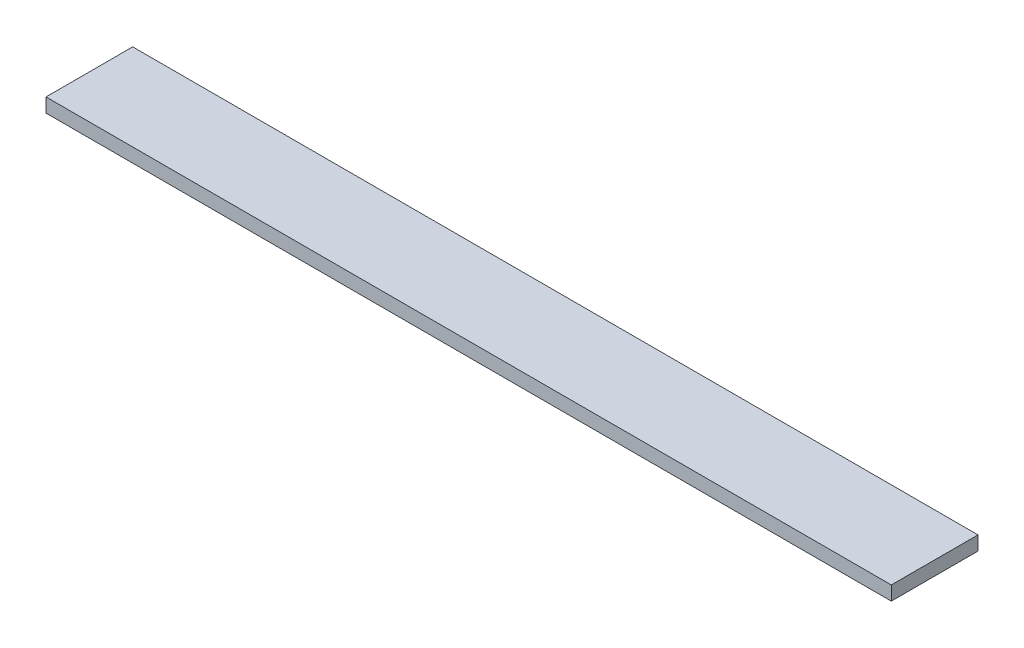
SolidWorks part; units mm, degrees
material "PE High Density"
ref_plane "Front Plane" through (0, 0, 0) normal (0, 0, 1) x (1, 0, 0)
ref_plane "Top Plane" through (0, 0, 0) normal (0, 1, 0) x (1, 0, 0)
ref_plane "Right Plane" through (0, 0, 0) normal (1, 0, 0) x (0, 0, -1)
sketch "Sketch1" plane through (0, 0, 0) normal (0, 1, 0) x (1, 0, 0)
  line L1 (-3139.4168, 959.2662) -> (-1839.2543, 959.2662)
  line L2 (-3139.4168, 959.2662) -> (-3139.4168, 825.9162)
  line L3 (-3139.4168, 825.9162) -> (-1839.2543, 825.9162)
  line L4 (-1839.2543, 959.2662) -> (-1839.2543, 825.9162)
  dimension "D1" = 1300.1625
  dimension "D2" = 133.35
extrude "Boss-Extrude1" add sketch "Sketch1" along normal blind 21.59
